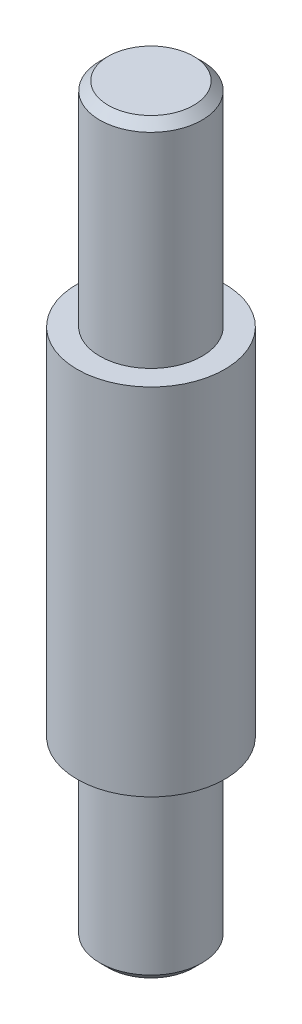
SolidWorks part; units mm, degrees
ref_plane "Front Plane" through (0, 0, 0) normal (0, 0, 1) x (1, 0, 0)
ref_plane "Top Plane" through (0, 0, 0) normal (0, 1, 0) x (1, 0, 0)
ref_plane "Right Plane" through (0, 0, 0) normal (1, 0, 0) x (0, 0, -1)
sketch "Sketch1" plane through (0, 0, 0) normal (1, 0, 0) x (0, 0, -1)
  line L0 (0, -33.401) -> (0, 33.401) construction
  line L1 (0, 33.401) -> (-3.81, 33.401)
  line L2 (-4.572, 32.639) -> (-4.572, 14.351)
  line L3 (-4.572, 14.351) -> (-6.604, 14.351)
  line L4 (-6.604, 14.351) -> (-6.604, -17.399)
  line L5 (-6.604, -17.399) -> (-4.572, -17.399)
  line L6 (-4.572, -17.399) -> (-4.572, -32.639)
  line L7 (-3.81, -33.401) -> (0, -33.401)
  line L8 (-15.6281, 0) -> (29.047, 0) construction
  line L9 (-3.81, 33.401) -> (-4.572, 32.639)
  line L10 (-4.572, -32.639) -> (-3.81, -33.401)
  line L11 (0, 33.401) -> (0, -33.401)
  point P3 (-5.588, -17.399)
  point P4 (0, 0)
  point P6 (-4.572, 33.401)
  point P11 (-4.572, -33.401)
  dimension "D1" = 66.802
  dimension "D2" = 16.002
  dimension "D3" = 4.572
  dimension "D4" = 6.604
  dimension "D5" = 0.762
  dimension "D6" = 45
  dimension "D7" = 0.762
  dimension "D8" = 45
  dimension "D9" = 4.572
  dimension "D10" = 19.05
revolve "Revolve1" add sketch "Sketch1" angle 360 about L11
